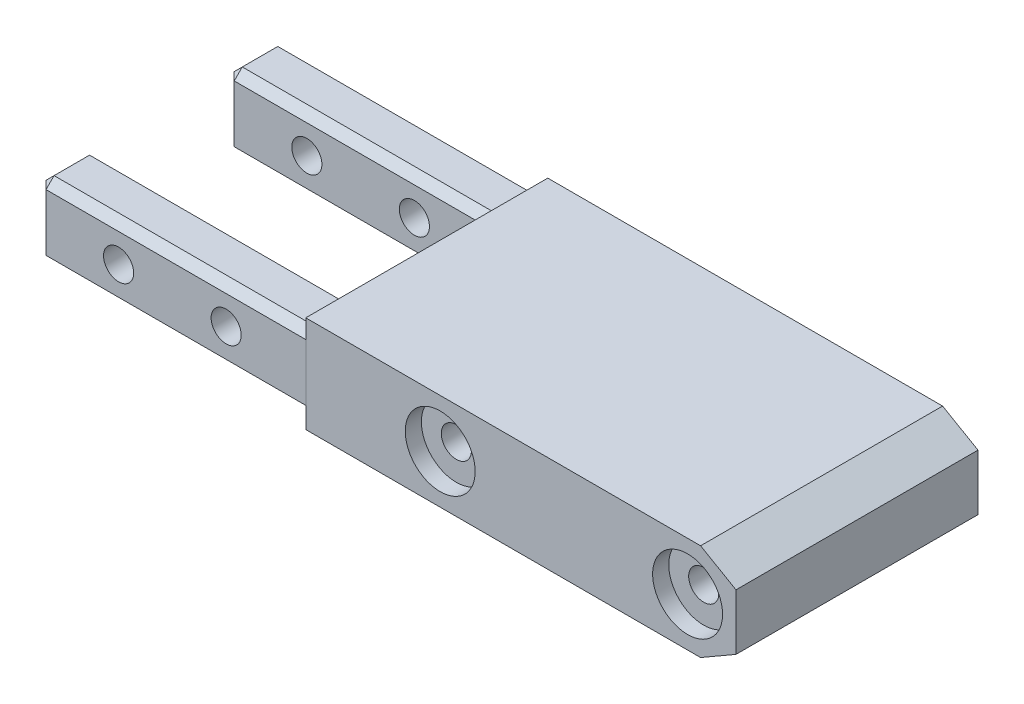
SolidWorks part; units mm, degrees
material "ABS"
ref_plane "Piano frontale" through (0, 0, 0) normal (0, 0, 1) x (1, 0, 0)
ref_plane "Piano superiore" through (0, 0, 0) normal (0, 1, 0) x (1, 0, 0)
ref_plane "Piano destro" through (0, 0, 0) normal (1, 0, 0) x (0, 0, -1)
sketch "Schizzo1" plane through (0, 0, 0) normal (0, 0, 1) x (1, 0, 0)
  line L1 (0, 0) -> (-80, 0)
  line L2 (0, 0) -> (0, 18)
  line L3 (0, 18) -> (-80, 18)
  line L4 (-80, 0) -> (-80, 18)
  dimension "D1" = 18
  dimension "D2" = 80
extrude "Estrusione-Estrusione1" add sketch "Schizzo1" along normal blind 45
chamfer "Smusso1" distance 3.8 angle 60 1 edges at (0, 18, 22.5)
chamfer "Smusso2" distance 3.8 angle 60 1 edges at (0, 0, 22.5)
sketch "Schizzo2" plane through (-80, 0, 0) normal (-1, 0, 0) x (0, 0, 1)
  line L0 (0, 18) -> (0, 0) construction
  line L1 (0.2, 15.8) -> (9.8, 15.8)
  line L2 (0.2, 15.8) -> (0.2, 2.2)
  line L3 (0.2, 2.2) -> (9.8, 2.2)
  line L4 (9.8, 15.8) -> (9.8, 2.2)
  line L5 (45, 18) -> (0, 18) construction
  line L6 (9.8, 2.2) -> (35.2, 2.2) construction
  line L7 (45, 18) -> (45, 0) construction
  line L8 (35.2, 15.8) -> (44.8, 15.8)
  line L9 (35.2, 15.8) -> (35.2, 2.2)
  line L10 (35.2, 2.2) -> (44.8, 2.2)
  line L11 (44.8, 15.8) -> (44.8, 2.2)
  dimension "D1" = 0.2
  dimension "D2" = 9.6
  dimension "D3" = 13.6
  dimension "D4" = 2.2
  dimension "D5" = 0.2
extrude "Estrusione-Estrusione2" add sketch "Schizzo2" along normal blind 50
chamfer "Smusso3" distance 1.5 angle 45 16 edges at (-130, 15.8, 40) (-105, 15.8, 44.8) (-130, 9, 44.8) (-105, 2.2, 44.8) (-130, 2.2, 40) (-105, 2.2, 35.2) (-130, 9, 35.2) (-105, 15.8, 35.2) (-130, 15.8, 5) (-105, 15.8, 9.8) (-130, 9, 9.8) (-105, 2.2, 9.8) (-130, 2.2, 5) (-105, 2.2, 0.2) (-130, 9, 0.2) (-105, 15.8, 0.2)
hole_wizard "Foro per Vite M4-1" positions "Schizzo3D1" profile "Schizzo3" hole size "M4" standard "ISO"
sketch3d "Schizzo3D1"
  line L0 (-95, 9, 0.2) -> (-128.5, 9, 0.2) construction
  line L1 (-128.5, 3.7, 0.2) -> (-128.5, 14.3, 0.2) construction
  point P0 (-115, 9, 0.2)
  point P2 (-95, 9, 0.2)
  dimension "D1" = 15
  dimension "D2" = 20
sketch "Schizzo3" plane through (-115, 9, 0.2) normal (1, 0, 0) x (0, 1, 0)
  line L0 (0, 0) -> (0, 51.6824)
  line L1 (0, 51.6824) -> (2.8, 50)
  line L2 (2.8, 50) -> (2.8, 0)
  line L5 (2.8, 0) -> (0, 0)
  line L10 (0, 51.6824) -> (-2.8, 50) construction
  line L11 (0, -6.35) -> (0, 107.95) construction
  dimension "Hole Dia." = 5.6
  dimension "Hole Depth" = 50
  dimension "Drill Angle" = 118
sketch "Schizzo4" plane through (0, 0, 45) normal (0, 0, 1) x (1, 0, 0)
  line L0 (-55, 9) -> (-9, 9) construction
  line L2 (0, 3.8) -> (0, 14.2) construction
  line L3 (-80, 18) -> (-80, 0) construction
  line L4 (-80, 0) -> (-6.5818, 0) construction
  point P0 (-9, 9)
  point P2 (-55, 9)
  dimension "D1" = 9
  dimension "D2" = 25
  dimension "D3" = 9
hole_wizard "Foro lamato per Bullone M5 a testa esagonale-1" positions "Schizzo4" profile "Schizzo5" counterbore size "M5" standard "ISO"
sketch "Schizzo5" plane through (-9, 9, 45) normal (1, 0, 0) x (0, -1, 0)
  line L0 (0, 0) -> (0, 51.6824)
  line L1 (0, 51.6824) -> (2.8, 50)
  line L2 (2.8, 50) -> (2.8, 3)
  line L3 (2.8, 3) -> (6.5, 3)
  line L4 (6.5, 3) -> (6.5, 0)
  line L5 (6.5, 0) -> (0, 0)
  line L10 (0, 51.6824) -> (-2.8, 50) construction
  line L11 (0, -6.35) -> (0, 107.95) construction
  dimension "Hole Dia." = 5.6
  dimension "Hole Depth" = 50
  dimension "C'Bore Dia." = 13
  dimension "C'Bore Depth" = 3
  dimension "Drill Angle" = 118
hole_wizard "Foro lamato per Bullone M5 a testa esagonale-2" positions "Schizzo3D2" profile "Schizzo6" counterbore size "M5" standard "ISO"
sketch3d "Schizzo3D2"
  line L0 (-9, 9, 0) -> (-9, 9, 42) construction
  line L1 (-55, 9, 0) -> (-55, 9, 42) construction
  point P0 (-9, 9, 0)
  point P2 (-55, 9, 0)
sketch "Schizzo6" plane through (-9, 9, 0) normal (1, 0, 0) x (0, 1, 0)
  line L0 (0, 0) -> (0, 51.6824)
  line L1 (0, 51.6824) -> (2.8, 50)
  line L2 (2.8, 50) -> (2.8, 3)
  line L3 (2.8, 3) -> (6.5, 3)
  line L4 (6.5, 3) -> (6.5, 0)
  line L5 (6.5, 0) -> (0, 0)
  line L10 (0, 51.6824) -> (-2.8, 50) construction
  line L11 (0, -6.35) -> (0, 107.95) construction
  dimension "Hole Dia." = 5.6
  dimension "Hole Depth" = 50
  dimension "C'Bore Dia." = 13
  dimension "C'Bore Depth" = 3
  dimension "Drill Angle" = 118
